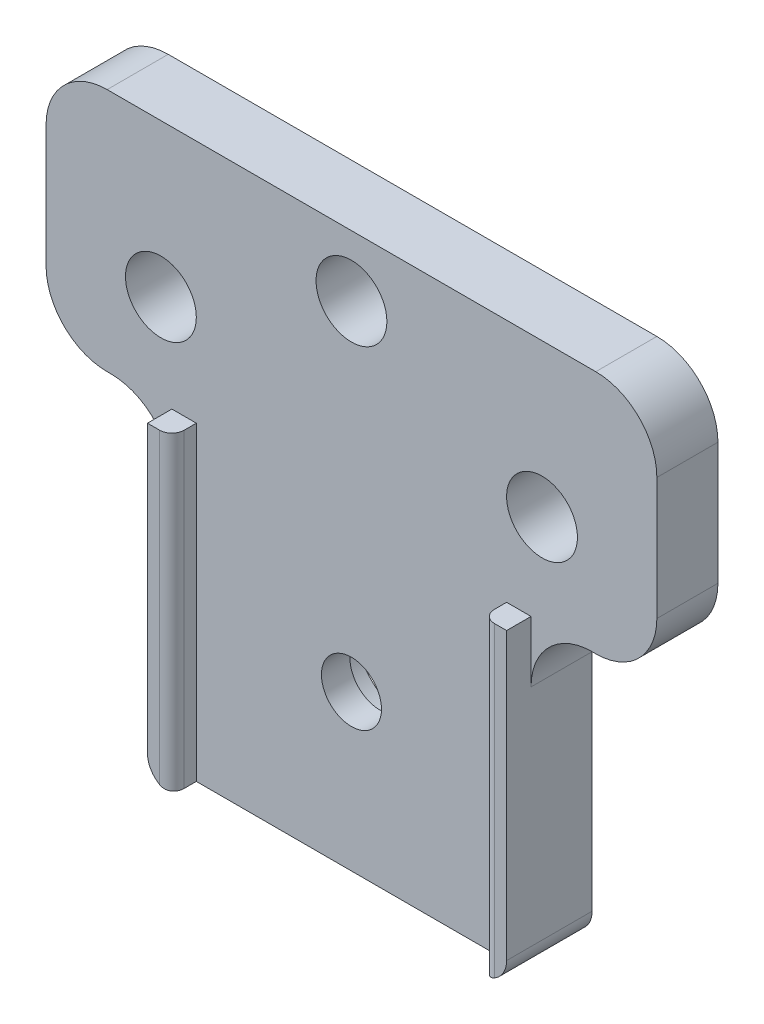
SolidWorks part; units mm, degrees
ref_plane "Front Plane" through (0, 0, 0) normal (0, 0, 1) x (1, 0, 0)
ref_plane "Top Plane" through (0, 0, 0) normal (0, 1, 0) x (1, 0, 0)
ref_plane "Right Plane" through (0, 0, 0) normal (1, 0, 0) x (0, 0, -1)
sketch "Sketch7" plane through (0, 0, 0) normal (0, 0, 1) x (1, 0, 0)
  line L1 (14.7, -20.2) -> (-14.7, -20.2)
  line L2 (14.7, -20.2) -> (14.7, 20.2)
  line L3 (14.7, 20.2) -> (-14.7, 20.2)
  line L4 (-14.7, -20.2) -> (-14.7, 20.2)
  line L5 (14.7, -20.2) -> (-14.7, 20.2) construction
  line L6 (14.7, 20.2) -> (-14.7, -20.2) construction
  point P0 (0, 0)
  dimension "D1" = 29.4
  dimension "D2" = 40.4
extrude "Boss-Extrude3" add sketch "Sketch7" along normal blind 5
sketch "Sketch8" plane through (0, -20.2, 0) normal (0, -1, 0) x (1, 0, 0)
  line L1 (-14.7, 5) -> (-12.7, 5)
  line L2 (-14.7, 5) -> (-14.7, 7)
  line L3 (-14.7, 7) -> (-13.7, 7)
  line L4 (-12.7, 5) -> (-12.7, 6)
  line L5 (14.7, 5) -> (12.7, 5)
  line L6 (14.7, 5) -> (14.7, 7)
  line L7 (14.7, 7) -> (13.7, 7)
  line L8 (12.7, 5) -> (12.7, 6)
  arc A0 (12.7, 6) -> (13.7, 7) centre (13.7, 6) cw
  arc A1 (-12.7, 6) -> (-13.7, 7) centre (-13.7, 6) ccw
  point P12 (12.7, 7)
  point P15 (-12.7, 7)
  dimension "D4" = 1
  dimension "D1" = 2
  dimension "D2" = 2
  dimension "D3" = 2
extrude "Boss-Extrude4" add sketch "Sketch8" against normal blind 25.4 contours L2 L1 L4 A1 L3 | L6 L5 L8 A0 L7
sketch "Sketch9" plane through (0, 0, 5) normal (0, 0, 1) x (1, 0, 0)
  line L0 (-12.7, -20.2) -> (12.7, -20.2) construction
  line L1 (15.6, 12.7) -> (-15.6, 12.7)
  line L2 (14.7, 20.2) -> (-14.7, 20.2) construction
  point P0 (0, -7.5)
  point P6 (0, 12.7)
  point P8 (0, 20.2)
  dimension "D1" = 12.7
  dimension "D2" = 31.2
  dimension "D3" = 0
sketch "Sketch11" plane through (0, 0, 5) normal (0, 0, 1) x (1, 0, 0)
  line L0 (15.6, 12.7) -> (-15.6, 12.7) construction
  line L1 (25, 5.2) -> (-25, 5.2)
  line L2 (25, 5.2) -> (25, 20.2)
  line L3 (25, 20.2) -> (-25, 20.2)
  line L4 (-25, 5.2) -> (-25, 20.2)
  line L5 (25, 5.2) -> (-25, 20.2) construction
  line L6 (25, 20.2) -> (-25, 5.2) construction
  line L7 (14.7, 20.2) -> (-14.7, 20.2) construction
  point P0 (0, 12.7)
  dimension "D1" = 0
  dimension "D2" = 50
extrude "Boss-Extrude5" add sketch "Sketch11" against normal up to surface (5 mm away) up to face at (0, 0, 0)
hole_wizard "CBORE for #8 Binding Head Machine Screw1" positions "Sketch14" profile "Sketch15" counterbore size "#8" standard "ANSI Inch" end condition through all
sketch "Sketch14" plane through (0, 0, 0) normal (0, 0, -1) x (-1, 0, 0)
  point P0 (0, -7.5)
sketch "Sketch15" plane through (0, -7.5, 0) normal (1, 0, 0) x (0, 1, 0)
  line L0 (0, 0) -> (0, 7)
  line L1 (0, 7) -> (2.4574, 7)
  line L3 (2.4574, 7) -> (2.4574, 2.667)
  line L4 (2.4574, 2.667) -> (4.7625, 2.667)
  line L5 (4.7625, 2.667) -> (4.7625, 0)
  line L7 (4.7625, 0) -> (0, 0)
  line L11 (0, -6.35) -> (0, 107.95) construction
  dimension "Thru Hole Dia." = 4.9149
  dimension "Thru Hole Depth" = 7
  dimension "C'Bore Dia." = 9.525
  dimension "C'Bore Depth" = 2.667
sketch "Sketch18" plane through (0, 20.2, 0) normal (0, 1, 0) x (1, 0, 0)
  line L1 (-25, 0) -> (25, 0)
  line L2 (-25, 0) -> (-25, -5)
  line L3 (-25, -5) -> (25, -5)
  line L4 (25, 0) -> (25, -5)
extrude "Boss-Extrude6" add sketch "Sketch18" along normal blind 5
sketch "Sketch19" plane through (0, 0, 5) normal (0, 0, 1) x (1, 0, 0)
  line L0 (-25, 25.2) -> (25, 25.2) construction
  point P0 (0, 20.2)
  dimension "D1" = 5
hole_wizard "M5 Clearance Hole1" positions "Sketch16" profile "Sketch17" hole size "M5" standard "ANSI Metric" end condition through all
sketch "Sketch16" plane through (0, 0, 5) normal (0, 0, 1) x (1, 0, 0)
  point P0 (-15.6, 12.7)
  point P3 (15.6, 12.7)
  point P6 (0, 20.2)
sketch "Sketch17" plane through (-15.6, 12.7, 5) normal (1, 0, 0) x (0, -1, 0)
  line L0 (0, 0) -> (0, 5)
  line L1 (0, 5) -> (2.9, 5)
  line L2 (2.9, 5) -> (2.9, 0)
  line L5 (2.9, 0) -> (0, 0)
  line L11 (0, -6.35) -> (0, 107.95) construction
  dimension "Thru Hole Dia." = 5.8
  dimension "Thru Hole Depth" = 5
fillet "Fillet2" radius 5 6 edges at (-14.7, 5.2, 2.5) (14.7, 5.2, 2.5) (25, 5.2, 2.5) (-25, 5.2, 2.5) (25, 25.2, 2.5) (-25, 25.2, 2.5)
fillet "Fillet3" radius 2 2 edges at (14.7, -20.2, 3.5) (-14.7, -20.2, 3.5)
